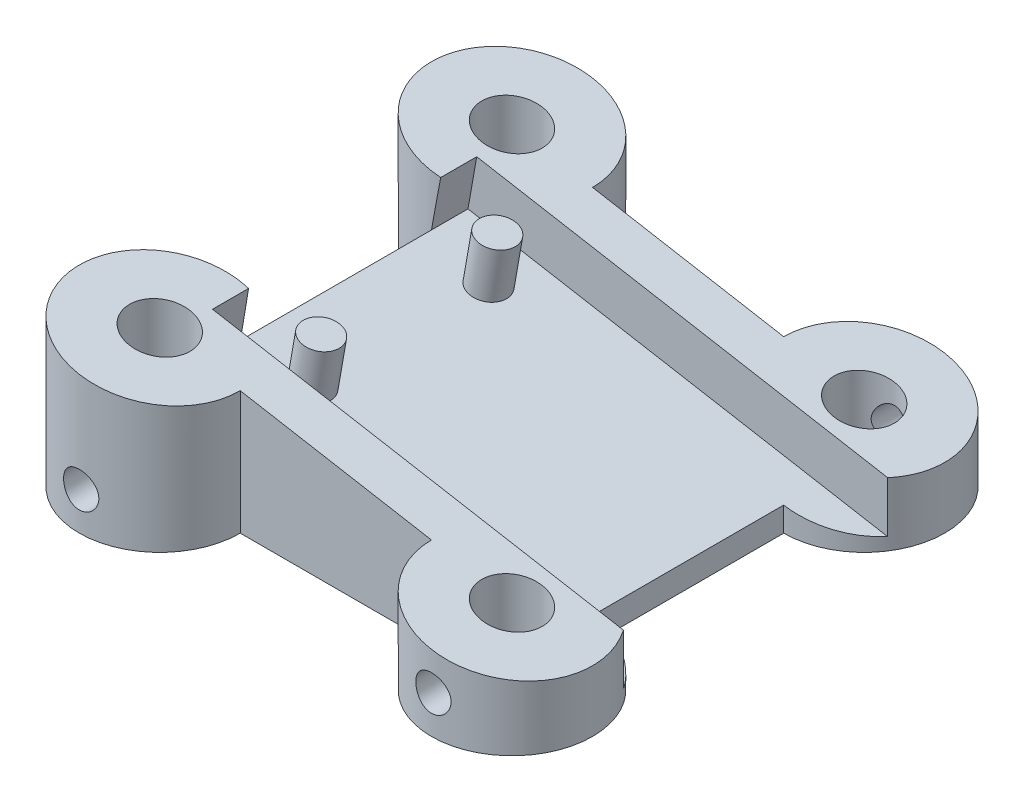
SolidWorks part; units mm, degrees
ref_plane "Front Plane" through (0, 0, 0) normal (0, 0, 1) x (1, 0, 0)
ref_plane "Top Plane" through (0, 0, 0) normal (0, 1, 0) x (1, 0, 0)
ref_plane "Right Plane" through (0, 0, 0) normal (1, 0, 0) x (0, 0, -1)
sketch "Sketch1" plane through (0, 0, 0) normal (0, 1, 0) x (1, 0, 0)
  line L0 (14, 28) -> (14, 0) construction
  line L1 (0, 0) -> (28, 0)
  line L2 (0, 0) -> (0, 28)
  line L3 (0, 28) -> (28, 28)
  line L4 (28, 0) -> (28, 28)
  line L5 (0, 14) -> (28, 14) construction
  point P9 (14, 14)
  dimension "D1" = 28
extrude "Boss-Extrude1" add sketch "Sketch1" along normal blind 10.9372
sketch "Sketch2" plane through (0, 0, 0) normal (0, 0, 1) x (1, 0, 0)
  line L0 (0, 10.9372) -> (28, 6)
  line L1 (0, 10.9372) -> (28, 10.9372) construction
  line L2 (28, 10.9372) -> (28, 0) construction
  line L3 (0, 10.9372) -> (28, 10.9372)
  line L4 (28, 10.9372) -> (28, 6)
  dimension "D2" = 6
  dimension "D3" = 10
extrude "Cut-Extrude1" cut sketch "Sketch2" against normal through all
sketch "Sketch3" plane through (1.8704, 10.6074, 0) normal (0.1736, 0.9848, 0) x (0.9848, -0.1736, 0)
  line L0 (-1.8992, 28) -> (-1.8992, 0) construction
  line L1 (-1.8992, 3.5) -> (48.1008, 3.5)
  line L2 (-1.8992, 3.5) -> (-1.8992, 24.5)
  line L3 (-1.8992, 24.5) -> (48.1008, 24.5)
  line L4 (48.1008, 3.5) -> (48.1008, 24.5)
  point P9 (-1.8992, 14)
  point P10 (-1.8992, 14)
  dimension "D1" = 21
  dimension "D2" = 50
extrude "Cut-Extrude2" cut sketch "Sketch3" against normal blind 4
ref_plane "Plane1" through (0, 10.9372, 0) normal (0, 1, 0) x (1, 0, 0)
sketch "Sketch11" plane through (1.1758, 6.6681, 0) normal (0.1736, 0.9848, 0) x (0.9848, -0.1736, 0)
  line L0 (27.238, 24.5) -> (-1.1939, 24.5) construction
  line L1 (27.238, 24.5) -> (27.238, 3.5) construction
  line L2 (-1.1939, 3.5) -> (27.238, 3.5) construction
  line L3 (27.238, 24.5) -> (-1.1939, 24.5) construction
  line L4 (27.238, 24.5) -> (27.238, 3.5) construction
  line L5 (-1.1939, 3.5) -> (27.238, 3.5) construction
  line L6 (13.0221, 3) -> (13.0221, 50003) construction
  line L7 (24.633, 14) -> (-49975.367, 14) construction
  circle A2 centre (4.0221, 21) radius 1.45
  circle A3 centre (4.0221, 7) radius 1.45
  point P6 (13.0221, 3.5)
  point P9 (27.238, 14)
  dimension "D4" = 2.9
  dimension "D5" = 9
  dimension "D6" = 7
extrude "Boss-Extrude2" add sketch "Sketch11" along normal blind 4
sketch "Sketch12" plane through (0, 10.9372, 0) normal (0, 1, 0) x (1, 0, 0)
  line L0 (0, 3.5) -> (0, 24.5) construction
  line L1 (0, 3.5) -> (28, 3.5) construction
  line L2 (0, 3.5) -> (0, 24.5) construction
  line L3 (0, 3.5) -> (28, 3.5) construction
  line L4 (0, 14) -> (50000, 14) construction
  line L5 (14, 4) -> (14, 50004) construction
  circle A0 centre (14, 14) radius 7
  point P7 (0, 14)
  point P10 (14, 3.5)
  dimension "D1" = 14
sketch "Sketch13" plane through (0, 0, 0) normal (0, -1, 0) x (1, 0, 0)
  line L0 (0, 0) -> (28, 0) construction
  line L1 (28, 0) -> (28, -28) construction
  line L2 (28, -28) -> (0, -28) construction
  line L3 (0, -28) -> (0, 0) construction
  line L4 (0, 0) -> (28, 0) construction
  line L5 (28, 0) -> (28, -28) construction
  line L6 (28, -28) -> (0, -28) construction
  line L7 (0, -28) -> (0, 0) construction
  line L8 (0, -14) -> (28, -14) construction
  line L9 (14, -28) -> (14, 0) construction
  circle A0 centre (0, 0) radius 2.4
  circle A1 centre (28, 0) radius 2.4
  circle A2 centre (28, -28) radius 2.4
  circle A3 centre (0, -28) radius 2.4
  dimension "D1" = 4.8
  dimension "D2" = 2
  dimension "D3" = 2
extrude "Cut-Extrude5" cut sketch "Sketch13" against normal through all
sketch "Sketch14" plane through (0, 0, 0) normal (0, -1, 0) x (1, 0, 0)
  line L0 (28, -3.5) -> (28, -2.4) construction
  line L1 (2.4, -28) -> (25.6, -28) construction
  line L2 (0, -3.5) -> (0, -24.5) construction
  circle A0 centre (0, 0) radius 2.4 construction
  circle A1 centre (0, 0) radius 2.4 construction
  circle A2 centre (0, 0) radius 6.4
  circle A3 centre (0, 0) radius 2.4
  circle A4 centre (28, 0) radius 2.4
  circle A5 centre (28, 0) radius 6.4
  circle A6 centre (28, -28) radius 2.4
  circle A7 centre (28, -28) radius 6.4
  circle A8 centre (0, -28) radius 2.4
  circle A9 centre (0, -28) radius 6.4
  dimension "D1" = 4
  dimension "D4" = 4.8
  dimension "D2" = 2
  dimension "D3" = 2
extrude "Boss-Extrude3" add sketch "Sketch14" against normal up to surface (10.9372 mm away)
sketch "Sketch15" plane through (0, 0, -28) normal (0, 0, -1) x (-1, 0, 0)
  line L0 (-21.6, 0) -> (-6.4, 0) construction
  line L1 (-21.9, 0) -> (-0.9, 0) construction
  line L4 (-14, 8.4686) -> (-14, 0) construction
  line L5 (-6.4, 9.8087) -> (-21.6, 7.1285) construction
  circle A0 centre (-28, 3) radius 1.4
  circle A1 centre (0, 3) radius 1.4
  point P4 (-28, 0)
  dimension "D1" = 2.8
  dimension "D2" = 3
extrude "Cut-Extrude6" cut sketch "Sketch15" along normal through all
sketch "Sketch16" plane through (0, 0, 0) normal (0, 0, 1) x (1, 0, 0)
  circle A0 centre (0, 3) radius 1.4 construction
  circle A1 centre (28, 3) radius 1.4 construction
  circle A2 centre (0, 3) radius 1.4
  circle A3 centre (28, 3) radius 1.4
extrude "Cut-Extrude7" cut sketch "Sketch16" along normal through all
sketch "Sketch18" plane through (1.8704, 10.6074, 0) normal (0.1736, 0.9848, 0) x (0.9848, -0.1736, 0)
  line L5 (-1.8992, 3.5) -> (25.6754, 3.5) construction
  line L8 (3.5416, 3.5) -> (21.0919, 3.5) construction
  line L9 (3.5416, 3.5) -> (21.0919, 3.5) construction
  line L22 (4.2469, 24.5) -> (-1.1939, 24.5)
  line L37 (6.0919, 3.5) -> (36.0919, 3.5)
  line L38 (6.0919, 3.5) -> (6.0919, 24.5)
  line L39 (6.0919, 24.5) -> (36.0919, 24.5)
  line L40 (36.0919, 3.5) -> (36.0919, 24.5)
  line L42 (-1.1939, 24.5) -> (-1.1939, 21.6)
  line L46 (-1.1939, 6.4) -> (-1.1939, 3.5)
  line L47 (-1.1939, 3.5) -> (4.2469, 3.5)
  line L49 (3.5416, 24.5) -> (21.0919, 24.5) construction
  ellipse E1 centre (-1.1939, 28) end of major axis (5.3048, 28) minor radius 6.4 (-1.1939, 21.6) -> (4.2469, 24.5) ccw construction
  ellipse E2 centre (-1.1939, 28) end of major axis (5.3048, 28) minor radius 6.4 (-1.1939, 21.6) -> (4.2469, 24.5) ccw
  ellipse E3 centre (-1.1939, 0) end of major axis (-7.6926, 0) minor radius 6.4 (4.2469, 3.5) -> (-1.1939, 6.4) ccw construction
  ellipse E4 centre (-1.1939, 0) end of major axis (5.3048, 0) minor radius 6.4 (4.2469, 3.5) -> (-1.1939, 6.4) ccw
  point P7 (21.0919, 3.5)
  dimension "D1" = 30
extrude "Cut-Extrude8" cut sketch "Sketch18" against normal up to surface (4 mm away) up to face at (6.5647, 5.7179, -21)
equation "\"TrackLength\"= 150"
equation "\"MarbleWidth\"= 13"
equation "\"MarbleTrackWidth\"= \"MarbleWidth\" - 1"
equation "\"TrackWidth\"= \"MarbleTrackWidth\" + ( 2 * 4 )"
equation "\"MarbleTrackLength\"= \"TrackLength\" - ( 2 * 8 )"
equation "\"MountWidth\"= \"TrackWidth\" + 8"
equation "\"D1@Sketch1\"=\"MountWidth\""
equation "\"D1@Boss-Extrude1\"=\"RampHeight\""
equation "\"RampDepth\"=6"
equation "\"RampAngle\"= 10"
equation "\"RampHeight\"= ( \"MountWidth\" * tan ( \"RampAngle\" ) ) + \"RampDepth\""
equation "\"D1@Sketch3\"=\"TrackWidth\" + 1"
equation "\"MountWidth\"= \"TrackWidth\" + 10"
equation "\"MountLength\"=66.6651"
